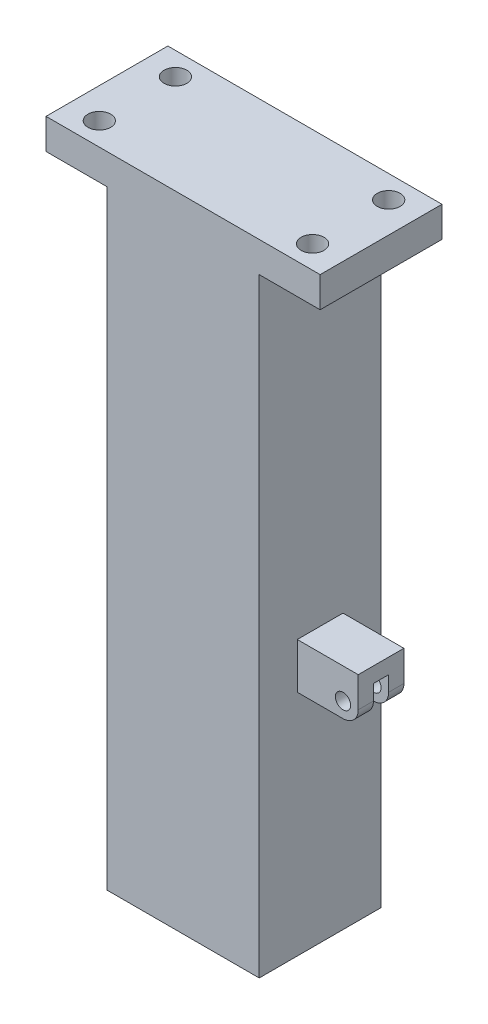
SolidWorks part; units mm, degrees
ref_plane "Front Plane" through (0, 0, 0) normal (0, 0, 1) x (1, 0, 0)
ref_plane "Top Plane" through (0, 0, 0) normal (0, 1, 0) x (1, 0, 0)
ref_plane "Right Plane" through (0, 0, 0) normal (1, 0, 0) x (0, 0, -1)
sketch "Sketch1" plane through (0, 0, 0) normal (0, 1, 0) x (1, 0, 0)
  line L1 (0, 0) -> (-180, 0)
  line L2 (0, 0) -> (0, 80)
  line L3 (0, 80) -> (-180, 80)
  line L4 (-180, 0) -> (-180, 80)
  dimension "D1" = 180
  dimension "D2" = 80
extrude "Boss-Extrude1" add sketch "Sketch1" along normal blind 20
sketch "Sketch2" plane through (0, 20, 0) normal (0, 1, 0) x (1, 0, 0)
  line L0 (-180, 80) -> (-180, 0) construction
  line L1 (-180, 0) -> (0, 0) construction
  line L2 (0, 80) -> (-180, 80) construction
  line L3 (0, 0) -> (0, 80) construction
  circle A0 centre (-160, 65) radius 7.5
  circle A1 centre (-160, 15) radius 7.5
  circle A2 centre (-20, 65) radius 7.5
  circle A3 centre (-20, 15) radius 7.5
  dimension "D1" = 15
  dimension "D2" = 15
  dimension "D3" = 15
  dimension "D4" = 15
  dimension "D5" = 20
  dimension "D6" = 15
  dimension "D7" = 15
  dimension "D8" = 20
  dimension "D9" = 15
  dimension "D10" = 20
  dimension "D11" = 15
  dimension "D12" = 20
extrude "Cut-Extrude1" cut sketch "Sketch2" against normal through all
sketch "Sketch3" plane through (0, 0, 0) normal (0, -1, 0) x (1, 0, 0)
  line L0 (-180, 0) -> (0, 0) construction
  line L1 (-140, 0) -> (-40, 0)
  line L2 (-140, 0) -> (-140, -80)
  line L3 (-140, -80) -> (-40, -80)
  line L4 (-40, 0) -> (-40, -80)
  line L5 (0, -80) -> (-180, -80) construction
  line L6 (-180, -80) -> (-180, 0) construction
  dimension "D1" = 100
  dimension "D2" = 40
extrude "Boss-Extrude2" add sketch "Sketch3" along normal blind 400
sketch "Sketch4" plane through (0, -400, 0) normal (0, -1, 0) x (1, 0, 0)
  line L0 (-140, -80) -> (-40, -80) construction
  line L1 (-140, 0) -> (-140, -80) construction
  line L2 (-40, -80) -> (-40, 0) construction
  line L3 (-40, 0) -> (-140, 0) construction
  line L4 (-140, 0) -> (-140, -80) construction
  circle A0 centre (-110, -25) radius 3.5
  circle A1 centre (-70, -25) radius 3.5
  circle A2 centre (-110, -55) radius 3.5
  circle A3 centre (-70, -55) radius 3.5
  dimension "D1" = 7
  dimension "D2" = 7
  dimension "D3" = 7
  dimension "D4" = 7
  dimension "D5" = 25
  dimension "D6" = 30
  dimension "D7" = 25
  dimension "D8" = 30
  dimension "D9" = 25
  dimension "D10" = 30
  dimension "D11" = 25
  dimension "D12" = 30
extrude "Cut-Extrude2" cut sketch "Sketch4" against normal blind 10
sketch "Sketch12" plane through (-40, 0, 0) normal (1, 0, 0) x (0, 0, -1)
  line L0 (80, -400) -> (0, -400) construction
  line L1 (25, -220) -> (55, -220)
  line L2 (25, -220) -> (25, -250)
  line L3 (25, -250) -> (55, -250)
  line L4 (55, -220) -> (55, -250)
  line L5 (80, -400) -> (80, 0) construction
  line L6 (0, -400) -> (0, 0) construction
  dimension "D1" = 30
  dimension "D2" = 150
  dimension "D3" = 25
  dimension "D4" = 25
extrude "Boss-Extrude6" add sketch "Sketch12" along normal blind 40
sketch "Sketch13" plane through (0, 0, -25) normal (0, 0, 1) x (1, 0, 0)
  line L0 (0, -250) -> (-40, -250) construction
  line L1 (0, -220) -> (0, -250) construction
  circle A0 centre (-10, -240) radius 5
  dimension "D1" = 10
  dimension "D2" = 10
  dimension "D3" = 10
extrude "Cut-Extrude7" cut sketch "Sketch13" against normal blind 30
sketch "Sketch14" plane through (0, 0, 0) normal (1, 0, 0) x (0, 0, -1)
  line L0 (25, -250) -> (55, -250) construction
  line L1 (35, -230) -> (45, -230)
  line L2 (35, -230) -> (35, -250)
  line L3 (35, -250) -> (45, -250)
  line L4 (45, -230) -> (45, -250)
  line L5 (25, -220) -> (25, -250) construction
  line L6 (55, -250) -> (55, -220) construction
  dimension "D1" = 20
  dimension "D2" = 10
  dimension "D3" = 10
extrude "Cut-Extrude8" cut sketch "Sketch14" against normal blind 20
fillet "Fillet4" radius 10 3 edges at (0, -250, -50) (0, -250, -30) (-20, -230, -40)
